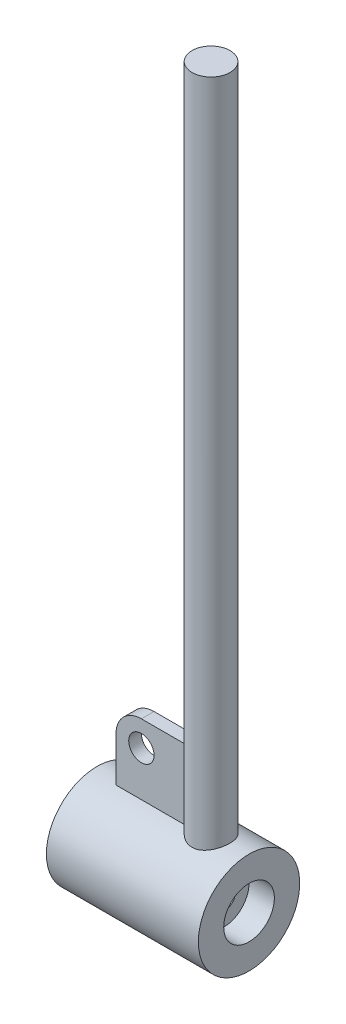
SolidWorks part; units mm, degrees
ref_plane "Front Plane" through (0, 0, 0) normal (0, 0, 1) x (1, 0, 0)
ref_plane "Top Plane" through (0, 0, 0) normal (0, 1, 0) x (1, 0, 0)
ref_plane "Right Plane" through (0, 0, 0) normal (1, 0, 0) x (0, 0, -1)
sketch "Sketch1" plane through (0, 0, 0) normal (0, 0, 1) x (1, 0, 0)
  line L0 (0, 0) -> (0, 25.4) construction
  line L1 (-58.6434, 0) -> (74.6132, 0) construction
  line L2 (-28.575, 12.7) -> (9.525, 12.7)
  line L3 (9.525, 12.7) -> (9.525, 6.35)
  line L4 (9.525, 6.35) -> (3.175, 6.35)
  line L5 (3.175, 6.35) -> (3.175, 3.0162)
  line L6 (3.175, 3.0162) -> (-15.875, 3.0162)
  line L7 (-15.875, 3.0162) -> (-15.875, 6.35)
  line L8 (-15.875, 6.35) -> (-28.575, 6.35)
  line L9 (-28.575, 6.35) -> (-28.575, 12.7)
  dimension "D1" = 6.35
  dimension "D2" = 6.0325
  dimension "D3" = 12.7
  dimension "D4" = 38.1
  dimension "D5" = 6.35
  dimension "D6" = 6.35
  dimension "D7" = 9.525
revolve "Revolve1" add sketch "Sketch1" angle 360 about L1
ref_plane "Plane1" through (0, 30, 0) normal (0, 1, 0) x (-1, 0, 0)
sketch "Sketch3" plane through (0, 30, 0) normal (0, 1, 0) x (-1, 0, 0)
  circle A0 centre (0, 0) radius 4.7625
  dimension "D1" = 9.525
extrude "Boss-Extrude1" add sketch "Sketch3" along normal blind 150 and the other way up to next
sketch "Sketch4" plane through (0, 0, 0) normal (0, 0, 1) x (1, 0, 0)
  line L0 (-28.575, 12.7) -> (-28.575, -12.7) construction
  line L1 (-3.175, 11.1125) -> (-22.225, 11.1125)
  line L2 (-3.175, 11.1125) -> (-3.175, 30.1625)
  line L3 (-3.175, 30.1625) -> (-15.875, 30.1625)
  line L4 (-22.225, 11.1125) -> (-22.225, 23.8125)
  line L5 (-4.7625, 12.7) -> (-28.575, 12.7) construction
  arc A0 (-15.875, 30.1625) -> (-22.225, 23.8125) centre (-15.875, 23.8125) ccw
  dimension "D5" = 6.35
  dimension "D1" = 19.05
  dimension "D2" = 6.35
  dimension "D3" = 1.5875
  dimension "D4" = 19.05
extrude "Boss-Extrude2" add sketch "Sketch4" along normal mid plane 3.175
sketch "Sketch5" plane through (0, 0, 1.5875) normal (0, 0, 1) x (1, 0, 0)
  circle A0 centre (-15.875, 23.8125) radius 3.175
  dimension "D1" = 6.35
extrude "Cut-Extrude1" cut sketch "Sketch5" against normal through all
